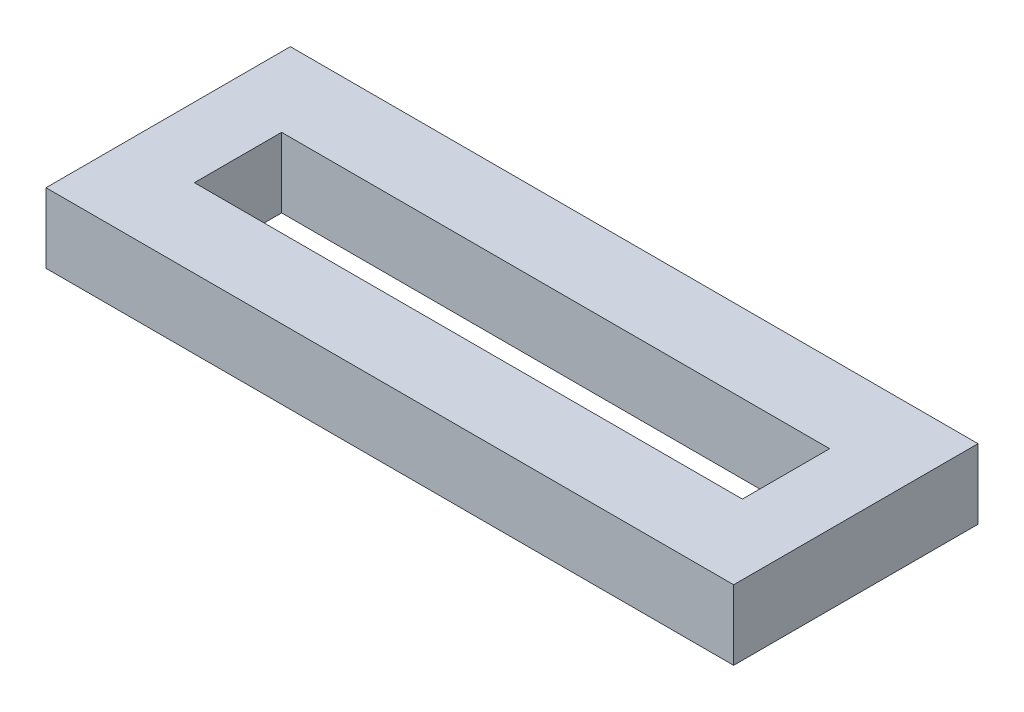
SolidWorks part; units mm, degrees
ref_plane "Alzado" through (0, 0, 0) normal (0, 0, 1) x (1, 0, 0)
ref_plane "Planta" through (0, 0, 0) normal (0, 1, 0) x (1, 0, 0)
ref_plane "Vista lateral" through (0, 0, 0) normal (1, 0, 0) x (0, 0, -1)
sketch "Croquis1" plane through (0, 0, 0) normal (0, 1, 0) x (1, 0, 0)
  line L1 (0, 0) -> (-39.4, 0)
  line L2 (0, 0) -> (0, -14)
  line L3 (0, -14) -> (-39.4, -14)
  line L4 (-39.4, 0) -> (-39.4, -14)
  line L5 (-4, -4.5) -> (-35.4, -4.5)
  line L6 (-4, -4.5) -> (-4, -9.5)
  line L7 (-4, -9.5) -> (-35.4, -9.5)
  line L8 (-35.4, -4.5) -> (-35.4, -9.5)
  point P9 (-4, -7)
  point P10 (0, -7)
  point P11 (-19.7, -4.5)
  point P12 (-19.7, 0)
  dimension "D1" = 14
  dimension "D2" = 39.4
  dimension "D3" = 5
  dimension "D4" = 4
extrude "Saliente-Extruir1" add sketch "Croquis1" along normal blind 4
